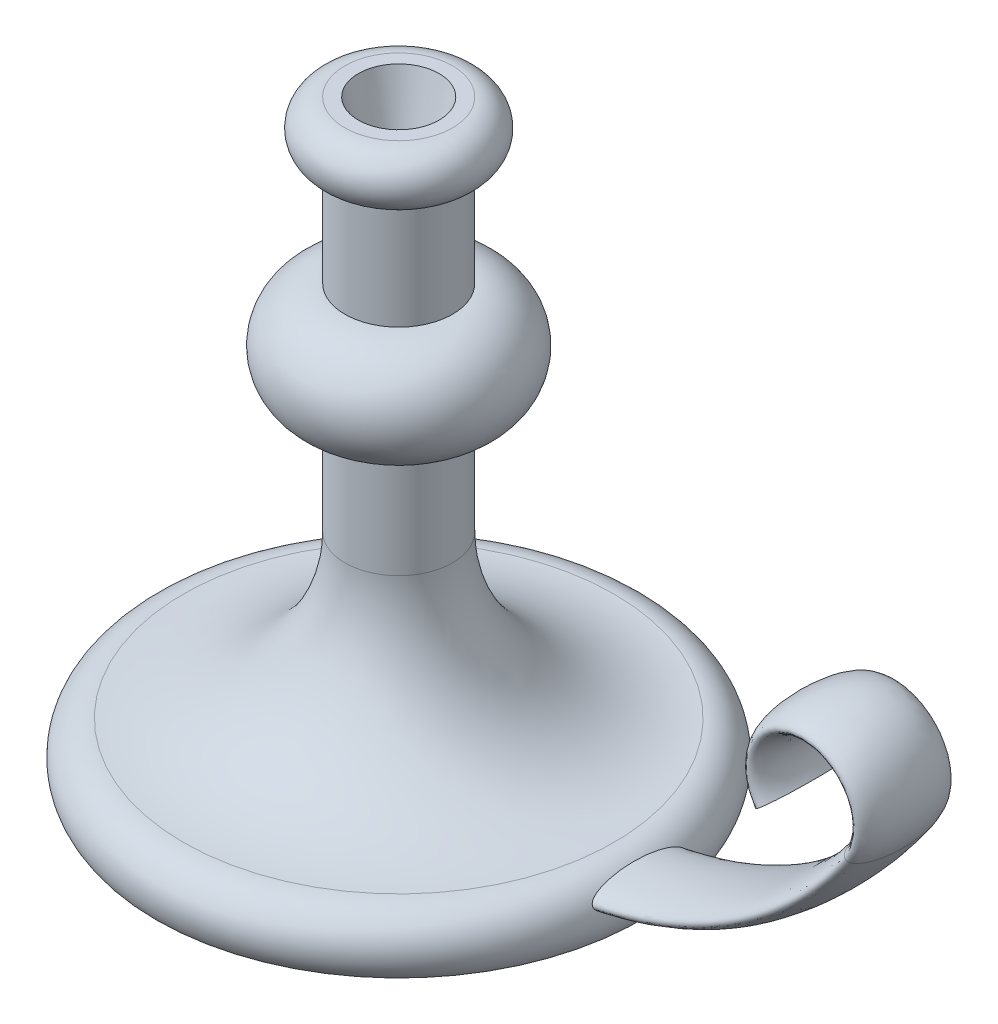
SolidWorks part; units mm, degrees
ref_plane "Front Plane" through (0, 0, 0) normal (0, 0, 1) x (1, 0, 0)
ref_plane "Top Plane" through (0, 0, 0) normal (0, 1, 0) x (1, 0, 0)
ref_plane "Right Plane" through (0, 0, 0) normal (1, 0, 0) x (0, 0, -1)
sketch "Sketch1" plane through (0, 0, 0) normal (0, 0, 1) x (1, 0, 0)
  line L0 (0, 0) -> (0, 220)
  line L1 (0, 220) -> (20, 220)
  line L2 (0, 0) -> (90, 0)
  line L3 (20, 200) -> (20, 160)
  line L4 (20, 120) -> (20, 80)
  arc A0 (20, 220) -> (20, 200) centre (20, 210) cw
  arc A1 (20, 160) -> (20, 120) centre (20, 140) cw
  arc A2 (20, 80) -> (80, 20) centre (80, 80) ccw
  arc A4 (80, 20) -> (90, 0) centre (80, 7.5) cw
  dimension "D4" = 10
  dimension "D5" = 20
  dimension "D7" = 40
  dimension "D8" = 60
  dimension "D9" = 12.5
  dimension "D1" = 220
  dimension "D2" = 20
  dimension "D3" = 90
  dimension "D6" = 40
revolve "Revolve1" add sketch "Sketch1" angle 360 about L0
sketch "Sketch2" plane through (0, 0, 0) normal (0, 0, 1) x (1, 0, 0)
  line L0 (0, 227.4356) -> (0, 175.1288) construction
  line L1 (0, 10) -> (60, 10)
  line L2 (0, 164) -> (0, 92) construction
  arc A0 (60, 10) -> (183.5921, 75) centre (60, 160) ccw
  arc A1 (183.5921, 75) -> (150.6342, 75) centre (167.1131, 86.3333) ccw
  dimension "D2" = 150
  dimension "D4" = 20
  dimension "D1" = 60
  dimension "D3" = 65
sketch "Sketch3" plane through (0, 0, 0) normal (1, 0, 0) x (0, 0, -1)
  ellipse E0 centre (0, 10) end of major axis (17.5, 10) minor radius 5
  dimension "D1" = 35
  dimension "D2" = 10
sketch "Sketch4" plane through (0, 0, 0) normal (1, 0, 0) x (0, 0, -1)
sweep "Sweep1" add profiles "Sketch3" path "Sketch2"
sketch "Sketch5" plane through (0, 220, 0) normal (0, 1, 0) x (1, 0, 0)
  circle A0 centre (0, 0) radius 15
  dimension "D1" = 30
extrude "Cut-Extrude1" cut sketch "Sketch5" against normal blind 25 draft 15
